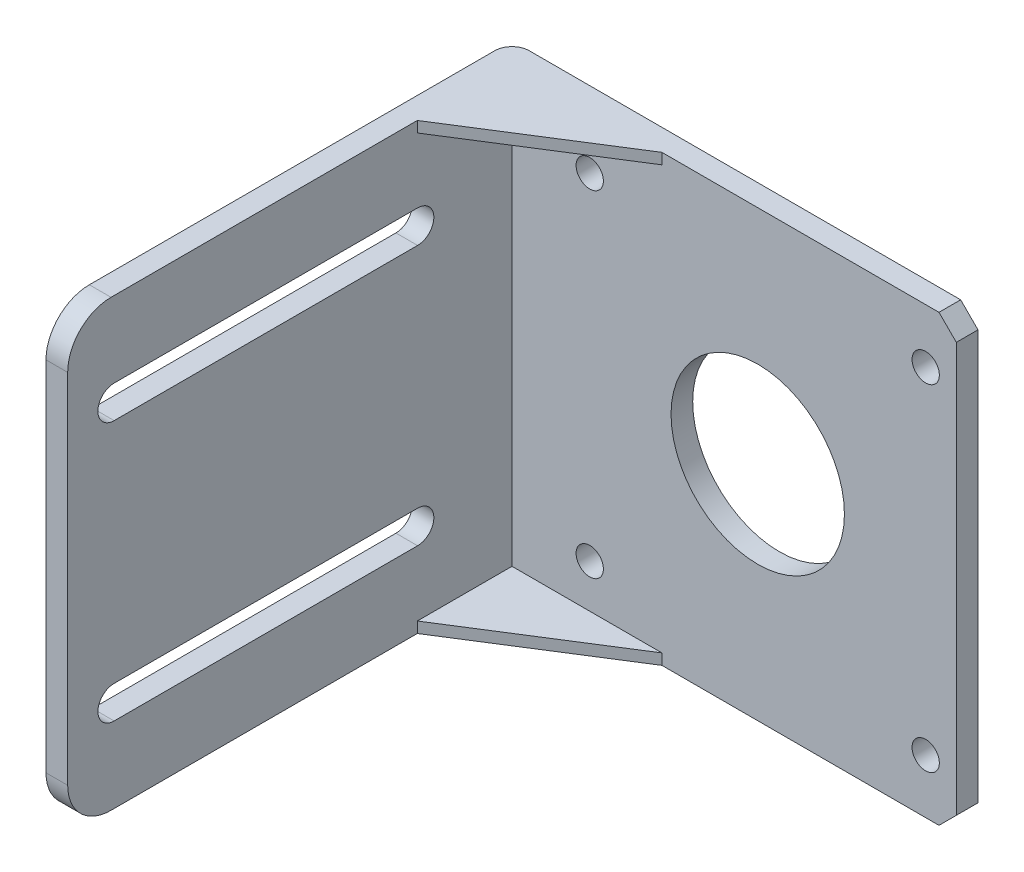
SolidWorks part; units mm, degrees
ref_plane "Front Plane" through (0, 0, 0) normal (0, 0, 1) x (1, 0, 0)
ref_plane "Top Plane" through (0, 0, 0) normal (0, 1, 0) x (1, 0, 0)
ref_plane "Right Plane" through (0, 0, 0) normal (1, 0, 0) x (0, 0, -1)
sketch "Sketch1" plane through (0, 0, 0) normal (0, 1, 0) x (1, 0, 0)
  line L0 (32.0136, 34.2558) -> (32.0136, 31.0808)
  line L1 (32.0136, 31.0808) -> (-33.0739, 31.0808)
  line L2 (-33.0739, 31.0808) -> (-33.0739, -34.0067)
  line L3 (-33.0739, -34.0067) -> (-36.2489, -34.0067)
  line L4 (-36.2489, -34.0067) -> (-36.2489, 31.7158)
  line L5 (-33.7089, 34.2558) -> (32.0136, 34.2558)
  arc A0 (-36.2489, 31.7158) -> (-33.7089, 34.2558) centre (-33.7089, 31.7158) cw
  point P8 (-36.2489, 34.2558)
  dimension "D5" = 2.54
  dimension "D1" = 68.2625
  dimension "D2" = 68.2625
  dimension "D3" = 3.175
  dimension "D4" = 3.175
extrude "Boss-Extrude1" add sketch "Sketch1" along normal blind 65.0875
sketch "Sketch2" plane through (0, 0, -34.2558) normal (0, 0, -1) x (-1, 0, 0)
  line L0 (-29.4736, 65.0875) -> (-32.0136, 62.5475)
  line L5 (-29.4736, 0) -> (-32.0136, 2.54)
  line L6 (-27.5273, 32.5437) -> (21.6852, 32.5438) construction
  line L11 (-29.4736, 65.0875) -> (-32.0136, 65.0875)
  line L12 (-27.5273, 57.15) -> (21.6852, 57.15) construction
  line L13 (-27.5273, 57.15) -> (-27.5273, 7.9375) construction
  line L14 (-27.5273, 7.9375) -> (21.6852, 7.9375) construction
  line L15 (21.6852, 57.15) -> (21.6852, 7.9375) construction
  line L16 (-27.5273, 57.15) -> (21.6852, 7.9375) construction
  line L17 (-27.5273, 7.9375) -> (21.6852, 57.15) construction
  line L18 (-32.0136, 65.0875) -> (-32.0136, 62.5475)
  line L19 (-32.0136, 2.54) -> (-32.0136, 0)
  line L20 (-32.0136, 0) -> (-29.4736, 0)
  circle A0 centre (-27.5273, 57.15) radius 2
  circle A1 centre (21.6852, 57.15) radius 2
  circle A2 centre (21.6852, 7.9375) radius 2
  circle A3 centre (-27.5273, 7.9375) radius 2
  circle A4 centre (-2.921, 32.5437) radius 12.7
  point P1 (-32.0136, 65.0875)
  point P3 (-32.0136, 0)
  point P16 (-2.921, 32.5437)
  dimension "D3" = 4
  dimension "D4" = 4
  dimension "D7" = 4
  dimension "D8" = 4
  dimension "D9" = 25.4
  dimension "D1" = 49.2125
  dimension "D2" = 49.2125
extrude "Cut-Extrude1" cut sketch "Sketch2" against normal up to surface (3.175 mm away) up to face at (-0.5301, 32.5437, -31.0808)
sketch "Sketch3" plane through (-36.2489, 0, 0) normal (-1, 0, 0) x (0, 0, 1)
  line L5 (27.6567, 65.0875) -> (34.0067, 65.0875)
  line L6 (34.0067, 65.0875) -> (34.0067, 58.7375)
  line L8 (34.0067, 6.35) -> (34.0067, 0)
  line L9 (34.0067, 0) -> (27.6567, 0)
  arc A0 (34.0067, 6.35) -> (27.6567, 0) centre (27.6567, 6.35) cw
  arc A1 (27.6567, 65.0875) -> (34.0067, 58.7375) centre (27.6567, 58.7375) cw
  point P11 (34.0067, 65.0875)
  dimension "D1" = 6.35
extrude "Cut-Extrude2" cut sketch "Sketch3" against normal up to surface (3.175 mm away) up to face at (-33.0739, 32.5437, 1.4629)
sketch "Sketch4" plane through (0, 65.0875, 0) normal (0, 1, 0) x (1, 0, 0)
  line L0 (-27.5484, 34.2558) -> (-36.2489, 34.2558) construction
  line L1 (29.4736, 34.2558) -> (-33.7089, 34.2558) construction
  line L2 (-36.2489, 24.0212) -> (-36.2489, 34.2558) construction
  line L3 (-36.2489, 31.7158) -> (-36.2489, -27.6567) construction
  line L4 (-36.2489, 34.2558) -> (-6.0864, 34.2558) construction
  line L5 (-36.2489, 31.7158) -> (-36.2489, 15.2058)
  line L6 (-36.2489, 15.2058) -> (-6.0864, 34.2558)
  line L7 (-6.0864, 34.2558) -> (-33.7089, 34.2558)
  arc A0 (-36.2489, 31.7158) -> (-33.7089, 34.2558) centre (-33.7089, 31.7158) cw
  dimension "D3" = 2.54
  dimension "D1" = 30.1625
  dimension "D2" = 19.05
extrude "Boss-Extrude2" add sketch "Sketch4" against normal blind 1.5875
ref_plane "Plane1" through (0, 32.5437, 0) normal (0, -1, 0) x (-1, 0, 0)
mirror "Mirror1" about plane through (0, 32.5437, 0) normal (0, -1, 0) of "Boss-Extrude2"
sketch "Sketch5" plane through (-36.2489, 0, 0) normal (-1, 0, 0) x (0, 0, 1)
  line L0 (-17.2504, 51.5937) -> (27.1996, 51.5937) construction
  line L1 (-17.2504, 53.975) -> (27.1996, 53.975)
  line L2 (-17.2504, 49.2125) -> (27.1996, 49.2125)
  line L3 (-31.7158, 32.5437) -> (34.0067, 32.5438) construction
  line L4 (-31.7158, 65.0875) -> (-31.7158, 0) construction
  line L5 (34.0067, 58.7375) -> (34.0067, 6.35) construction
  line L6 (-31.7158, 65.0875) -> (27.6567, 65.0875) construction
  line L7 (-17.2504, 13.4937) -> (27.1996, 13.4938) construction
  line L8 (-17.2504, 11.1125) -> (27.1996, 11.1125)
  line L9 (-17.2504, 15.875) -> (27.1996, 15.875)
  arc A0 (-17.2504, 53.975) -> (-17.2504, 49.2125) centre (-17.2504, 51.5937) ccw
  arc A1 (27.1996, 49.2125) -> (27.1996, 53.975) centre (27.1996, 51.5937) ccw
  arc A2 (-17.2504, 11.1125) -> (-17.2504, 15.875) centre (-17.2504, 13.4937) cw
  arc A3 (27.1996, 15.875) -> (27.1996, 11.1125) centre (27.1996, 13.4938) cw
  point P2 (4.9746, 51.5937)
  point P17 (4.9746, 13.4938)
  dimension "D1" = 4.7625
  dimension "D2" = 44.45
  dimension "D3" = 11.1125
extrude "Cut-Extrude3" cut sketch "Sketch5" against normal up to surface (3.175 mm away) up to face at (-33.0739, 32.5437, -0.5049)
